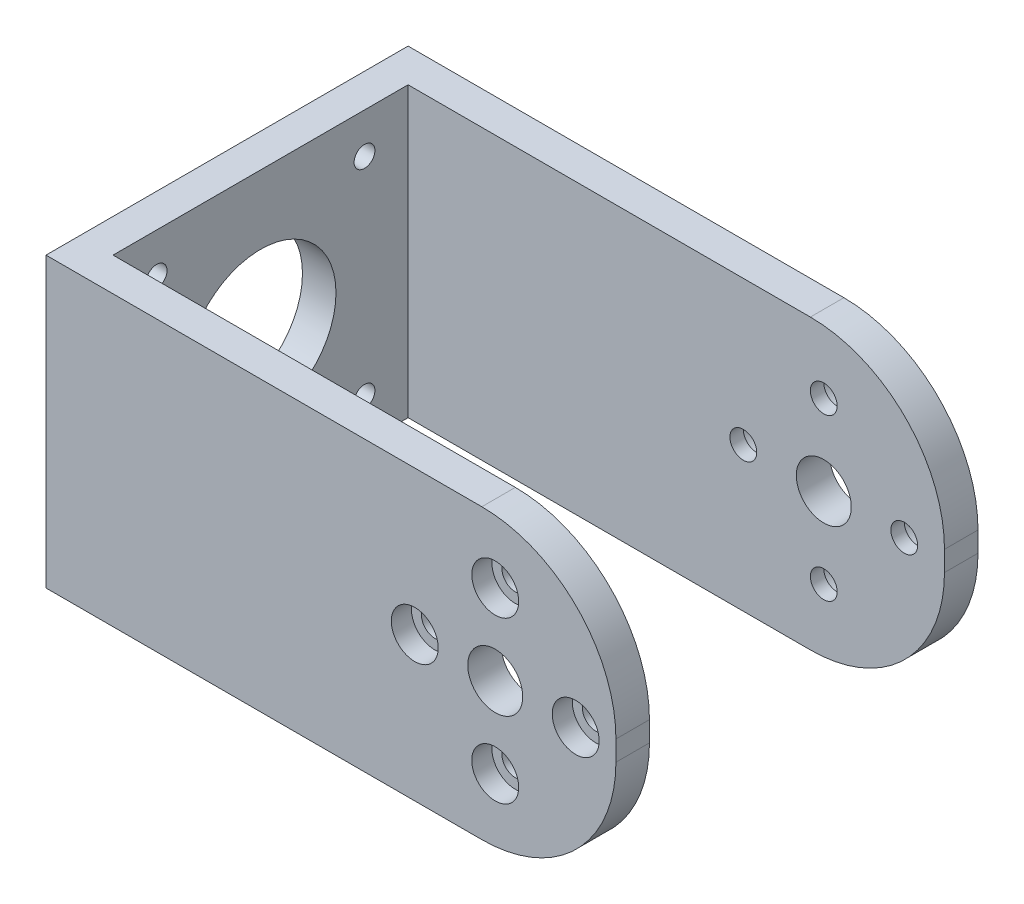
SolidWorks part; units mm, degrees
ref_plane "Front Plane" through (0, 0, 0) normal (0, 0, 1) x (1, 0, 0)
ref_plane "Top Plane" through (0, 0, 0) normal (0, 1, 0) x (1, 0, 0)
ref_plane "Right Plane" through (0, 0, 0) normal (1, 0, 0) x (0, 0, -1)
sketch "Sketch1" plane through (0, 0, 0) normal (1, 0, 0) x (0, 0, -1)
  line L1 (27, -21.5) -> (-27, -21.5)
  line L2 (27, -21.5) -> (27, 21.5)
  line L3 (27, 21.5) -> (-27, 21.5)
  line L4 (-27, -21.5) -> (-27, 21.5)
  line L5 (27, -21.5) -> (-27, 21.5) construction
  line L6 (27, 21.5) -> (-27, -21.5) construction
  point P0 (0, 0)
  dimension "D1" = 43
  dimension "D2" = 54
extrude "Boss-Extrude1" add sketch "Sketch1" along normal blind 5
sketch "Sketch2" plane through (5, 0, 0) normal (1, 0, 0) x (0, 0, -1)
  line L1 (-15.5, -15.5) -> (15.5, -15.5) construction
  line L2 (-15.5, -15.5) -> (-15.5, 15.5) construction
  line L3 (-15.5, 15.5) -> (15.5, 15.5) construction
  line L4 (15.5, -15.5) -> (15.5, 15.5) construction
  line L5 (-15.5, -15.5) -> (15.5, 15.5) construction
  line L6 (-15.5, 15.5) -> (15.5, -15.5) construction
  circle A0 centre (-15.5, 15.5) radius 1.55
  circle A1 centre (15.5, 15.5) radius 1.55
  circle A2 centre (15.5, -15.5) radius 1.55
  circle A3 centre (-15.5, -15.5) radius 1.55
  circle A4 centre (0, 0) radius 11.25
  point P0 (0, 0)
  point P16 (0, 0)
  dimension "D3" = 3.1
  dimension "D5" = 22.5
  dimension "D1" = 31
  dimension "D2" = 31
  dimension "D4" = 4
extrude "Cut-Extrude1" cut sketch "Sketch2" against normal up to next
sketch "Sketch4" plane through (5, 0, 0) normal (1, 0, 0) x (0, 0, -1)
  line L0 (-27, -21.5) -> (27, -21.5) construction
  line L1 (-27, 21.5) -> (-22, 21.5)
  line L2 (-27, 21.5) -> (-27, -21.5)
  line L3 (-27, -21.5) -> (-22, -21.5)
  line L4 (-22, 21.5) -> (-22, -21.5)
  line L5 (-24.5, -21.5) -> (-24.5, 21.5) construction
  line L6 (-27, 0) -> (-22, 0) construction
  point P80 (-24.5, 0)
  dimension "D1" = 5
extrude "Boss-Extrude2" add sketch "Sketch4" along normal blind 80
sketch "Sketch6" plane through (0, 0, 27) normal (0, 0, 1) x (1, 0, 0)
  line L0 (67, 0) -> (0, 0) construction
  circle A0 centre (67, 0) radius 12 construction
  circle A1 centre (67, 12) radius 2
  circle A2 centre (79, 0) radius 2
  circle A3 centre (67, -12) radius 2
  circle A4 centre (55, 0) radius 2
  circle A5 centre (67, 0) radius 4.1
  dimension "D1" = 24
  dimension "D3" = 4
  dimension "D4" = 4
  dimension "D5" = 8.2
  dimension "D2" = 67
extrude "Cut-Extrude2" cut sketch "Sketch6" against normal up to next
sketch "Sketch7" plane through (0, 0, 27) normal (0, 0, 1) x (1, 0, 0)
  line L0 (67, 12) -> (67, -12) construction
  line L1 (55, 0) -> (79, 0) construction
  circle A0 centre (67, 12) radius 3.5
  circle A1 centre (79, 0) radius 3.5
  circle A2 centre (67, -12) radius 3.5
  circle A3 centre (55, 0) radius 3.5
  dimension "D1" = 7
  dimension "D2" = 7
  dimension "D3" = 7
  dimension "D4" = 7
extrude "Cut-Extrude3" cut sketch "Sketch7" against normal blind 3
mirror "Mirror2" about plane through (0, 0, 0) normal (0, 0, 1) of "Cut-Extrude2", "Cut-Extrude3", "Boss-Extrude2"
fillet "Fillet1" radius 20 4 edges at (85, 21.5, -24.5) (85, -21.5, -24.5) (85, -21.5, 24.5) (85, 21.5, 24.5)
